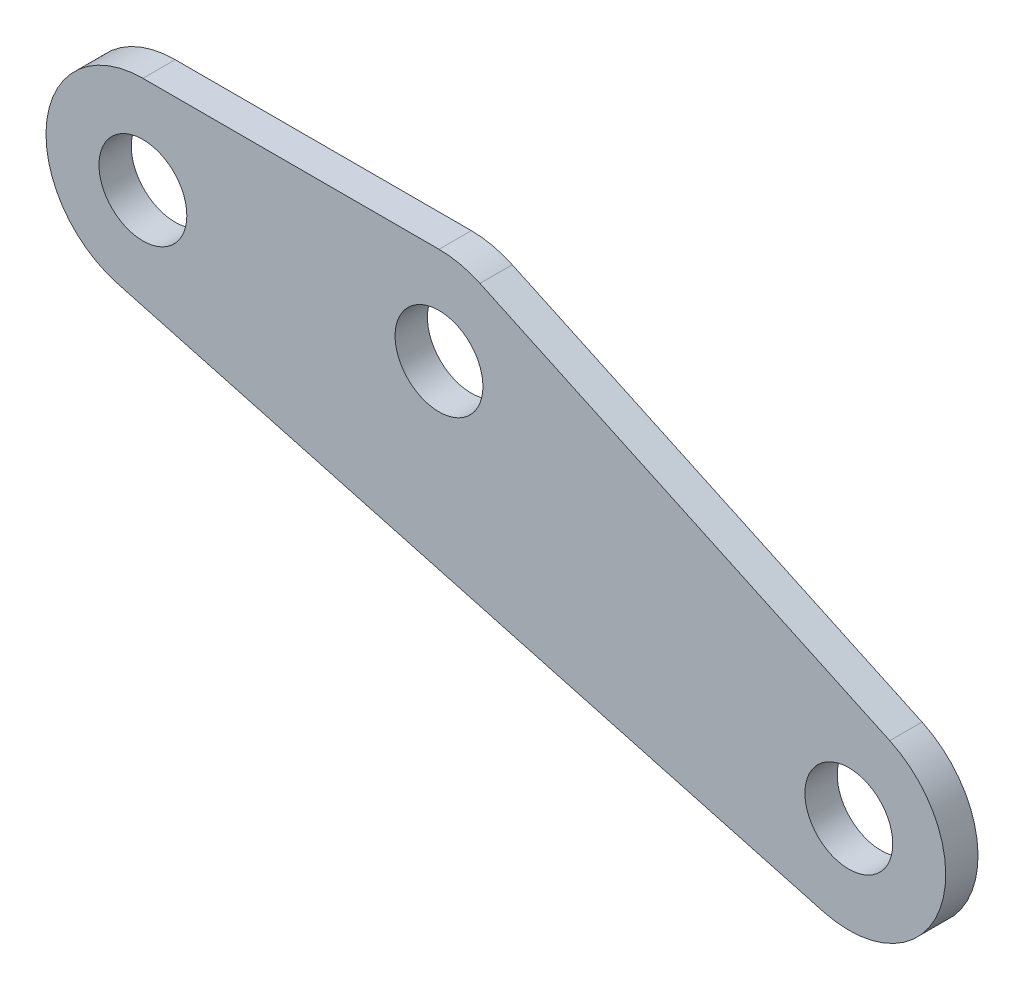
SolidWorks part; units mm, degrees
ref_plane "Front Plane" through (0, 0, 0) normal (0, 0, 1) x (1, 0, 0)
ref_plane "Top Plane" through (0, 0, 0) normal (0, 1, 0) x (1, 0, 0)
ref_plane "Right Plane" through (0, 0, 0) normal (1, 0, 0) x (0, 0, -1)
sketch "Sketch1" plane through (0, 0, 0) normal (0, 0, 1) x (1, 0, 0)
  line L2 (16.5669, 4.3163) -> (36.7096, -5.0764)
  line L3 (14.5542, 4.7625) -> (0, 4.7625)
  line L4 (-1.2445, -4.597) -> (33.4524, -13.9897)
  circle A0 centre (0, 0) radius 2.159
  circle A1 centre (14.5542, 0) radius 2.159
  circle A2 centre (34.6969, -9.3927) radius 2.159
  arc A3 (0, 4.7625) -> (-1.2445, -4.597) centre (0, 0) ccw
  arc A4 (16.5669, 4.3163) -> (14.5542, 4.7625) centre (14.5542, 0) ccw
  arc A5 (33.4524, -13.9897) -> (36.7096, -5.0764) centre (34.6969, -9.3927) ccw
  point P5 (7.2771, -11.4386)
  point P8 (15.2503, -11.0739)
  point P9 (14.5542, -11.631)
  point P16 (34.0073, -9.0977)
  point P17 (20.0937, -12.5013)
  point P18 (23.2264, -17.2638)
  point P19 (34.8417, -10.5226)
  point P20 (34.1976, -10.5657)
  point P21 (34.1728, -10.4433)
  dimension "D1" = 4.318
  dimension "D2" = 14.5542
  dimension "D3" = 9.525
  dimension "D6" = 4.318
  dimension "D4" = 22.225
  dimension "D5" = 155
extrude "Boss-Extrude1" add sketch "Sketch1" along normal blind 1.5875
